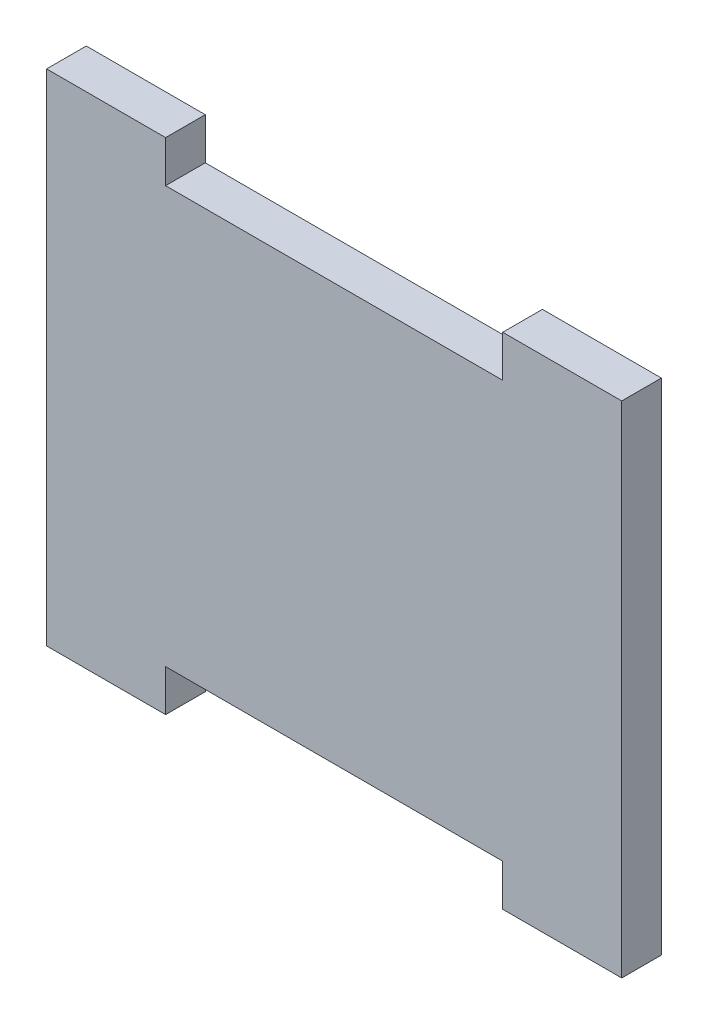
SolidWorks part; units mm, degrees
ref_plane "前视基准面" through (0, 0, 0) normal (0, 0, 1) x (1, 0, 0)
ref_plane "上视基准面" through (0, 0, 0) normal (0, 1, 0) x (1, 0, 0)
ref_plane "右视基准面" through (0, 0, 0) normal (1, 0, 0) x (0, 0, -1)
other "Configuration Table"
sketch "草图2" plane through (0, 0, 0) normal (0, 0, 1) x (1, 0, 0)
  line L0 (-24.5823, -10.5) -> (4.4177, -10.5)
  line L1 (4.4177, -10.5) -> (4.4177, 10.5)
  line L2 (4.4177, 10.5) -> (-24.5823, 10.5)
  line L3 (-24.5823, 10.5) -> (-24.5823, -10.5)
  line L4 (-33.3922, 0) -> (33.3922, 0) construction
  line L5 (-10.0823, 15.5654) -> (-10.0823, -16.292) construction
  line L6 (-24.5823, -12.6) -> (-24.5823, -10.5)
  line L7 (-18.5823, -12.6) -> (-24.5823, -12.6)
  line L8 (-1.5823, -10.5) -> (-1.5823, -12.6)
  line L9 (-10.0823, -15.5654) -> (-10.0823, 16.292) construction
  line L10 (-24.5823, -10.5) -> (-24.5823, -12.6)
  line L11 (-24.5823, -10.5) -> (-24.5823, -12.6)
  line L12 (4.4177, -10.5) -> (4.4177, -12.6)
  line L13 (-1.5823, -12.6) -> (4.4177, -12.6)
  line L14 (4.4177, -12.6) -> (4.4177, -10.5)
  line L15 (-18.5823, -10.5) -> (-18.5823, -12.6)
  line L16 (-18.5823, 10.5) -> (-18.5823, 12.6)
  line L17 (-18.5823, 12.6) -> (-24.5823, 12.6)
  line L18 (-24.5823, 12.6) -> (-24.5823, 10.5)
  line L19 (-1.5823, 12.6) -> (4.4177, 12.6)
  line L20 (-1.5823, 10.5) -> (-1.5823, 12.6)
  line L21 (4.4177, 10.5) -> (4.4177, 12.6)
  point P14 (-10.0823, -12.6)
  point P21 (-10.0823, 12.6)
  dimension "D3" = 6
  dimension "D1" = 21
  dimension "D2" = 29
  dimension "D8" = 2.1
extrude "凸台-拉伸1" add sketch "草图2" along normal blind 2 contours L2 L3 L0 L1 | L17 L18 L2 L16 | L2 L21 L19 L20 | L15 L0 L6 L7 | L8 L13 L12 L0
